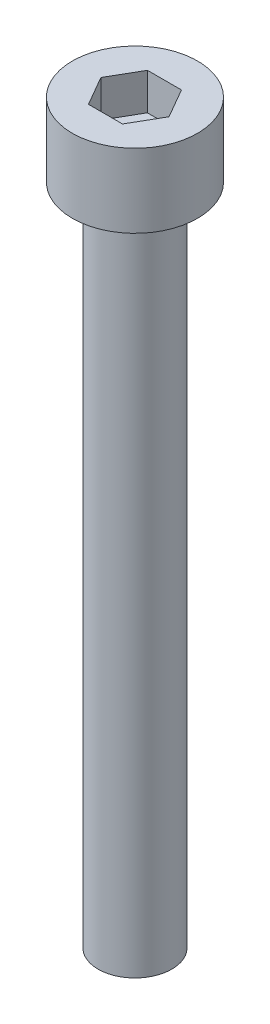
SolidWorks part; units mm, degrees
material "AISI 304"
ref_plane "Front Plane" through (0, 0, 0) normal (0, 0, 1) x (1, 0, 0)
ref_plane "Top Plane" through (0, 0, 0) normal (0, 1, 0) x (1, 0, 0)
ref_plane "Right Plane" through (0, 0, 0) normal (1, 0, 0) x (0, 0, -1)
sketch "Sketch1" plane through (0, 0, 0) normal (0, 0, 1) x (1, 0, 0)
  line L0 (0, 61.6916) -> (0, -59.3578) construction
  line L1 (0, -45) -> (2.5, -45)
  line L2 (2.5, -45) -> (2.5, 0)
  line L3 (2.5, 0) -> (4.25, 0)
  line L4 (4.25, 0) -> (4.25, 5)
  line L5 (4.25, 5) -> (0, 5)
  line L6 (0, 5) -> (0, -45)
  dimension "D1" = 45
  dimension "D2" = 8.5
  dimension "D3" = 5
  dimension "D4" = 5
revolve "Revolve1" add sketch "Sketch1" angle 360 about L0
sketch "Sketch2" plane through (0, 5, 0) normal (0, 1, 0) x (-1, 0, 0)
  line L1 (-1.1547, -2) -> (1.1547, -2)
  line L2 (1.1547, -2) -> (2.3094, 0)
  line L3 (2.3094, 0) -> (1.1547, 2)
  line L4 (1.1547, 2) -> (-1.1547, 2)
  line L5 (-1.1547, 2) -> (-2.3094, 0)
  line L6 (-2.3094, 0) -> (-1.1547, -2)
  circle A0 centre (0, 0) radius 2 construction
  dimension "D1" = 4
extrude "Cut-Extrude1" cut sketch "Sketch2" against normal blind 2.5
